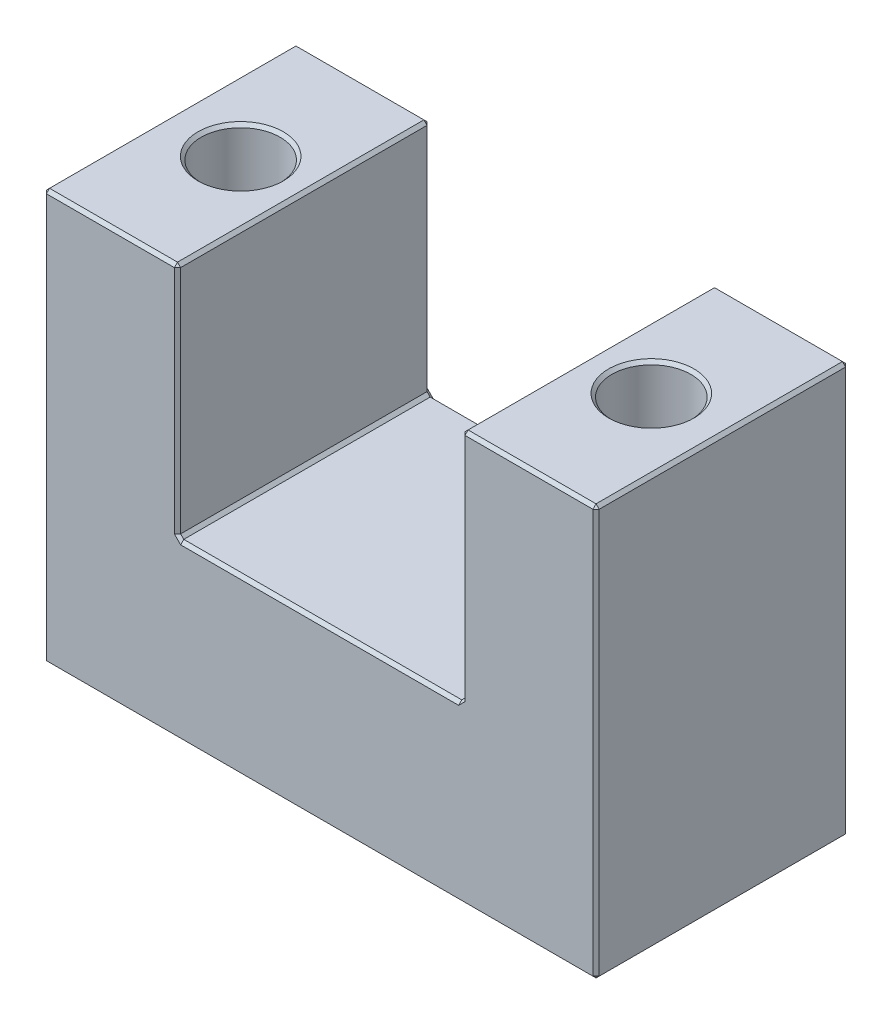
SolidWorks part; units mm, degrees
ref_plane "Front Plane" through (0, 0, 0) normal (0, 0, 1) x (1, 0, 0)
ref_plane "Top Plane" through (0, 0, 0) normal (0, 1, 0) x (1, 0, 0)
ref_plane "Right Plane" through (0, 0, 0) normal (1, 0, 0) x (0, 0, -1)
sketch "Sketch1" plane through (0, 0, 0) normal (0, 0, 1) x (1, 0, 0)
  line L0 (0, 0) -> (-17.5, 0)
  line L1 (-17.5, 0) -> (-17.5, 26)
  line L2 (-17.5, 26) -> (-9, 26)
  line L3 (-9, 26) -> (-9, 11)
  line L4 (-9, 11) -> (0, 11)
  line L5 (0, 11) -> (0, 0)
  dimension "D1" = 17.5
  dimension "D2" = 11
  dimension "D3" = 15
  dimension "D4" = 9
extrude "Boss-Extrude1" add sketch "Sketch1" along normal mid plane 16
mirror "Mirror1" about plane through (0, 0, 0) normal (1, 0, 0) of "Boss-Extrude1"
sketch "Sketch2" plane through (0, 26, 0) normal (0, 1, 0) x (1, 0, 0)
  line L0 (-17.5, 0) -> (0, 0) construction
  line L1 (-17.5, -8) -> (-17.5, 8) construction
  line L2 (0, 0) -> (17.5, 0) construction
  line L3 (17.5, -8) -> (17.5, 8) construction
  line L4 (-9, -8) -> (-17.5, -8) construction
  circle A0 centre (-13, 0) radius 2.5
  circle A1 centre (13, 0) radius 2.5
  point P14 (13.5326, 0)
  dimension "D2" = 5
  dimension "D3" = 5
  dimension "D1" = 4.5
  dimension "D4" = 8
  dimension "D5" = 4.5
extrude "Cut-Extrude1" cut sketch "Sketch2" against normal through all
chamfer "Chamfer1" distance 0.2 angle 45 28 edges at (13, 26, 2.5) (13, 0, 2.5) (-13, 26, 2.5) (-13, 0, 2.5) (-13.25, 26, -8) (-13.25, 26, 8) (0, 0, -8) (0, 0, 8) (13.25, 26, -8) (-17.5, 26, 0) (-17.5, 13, -8) (-17.5, 13, 8) (-17.5, 0, 0) (17.5, 0, 0) (17.5, 13, -8) (17.5, 26, 0) (9, 26, 0) (9, 18.5, -8) (-9, 26, 0) (-9, 18.5, -8) (-9, 18.5, 8) (9, 11, 0) (0, 11, -8) (0, 11, 8) (-9, 11, 0) (9, 18.5, 8) (13.25, 26, 8) (17.5, 13, 8)
